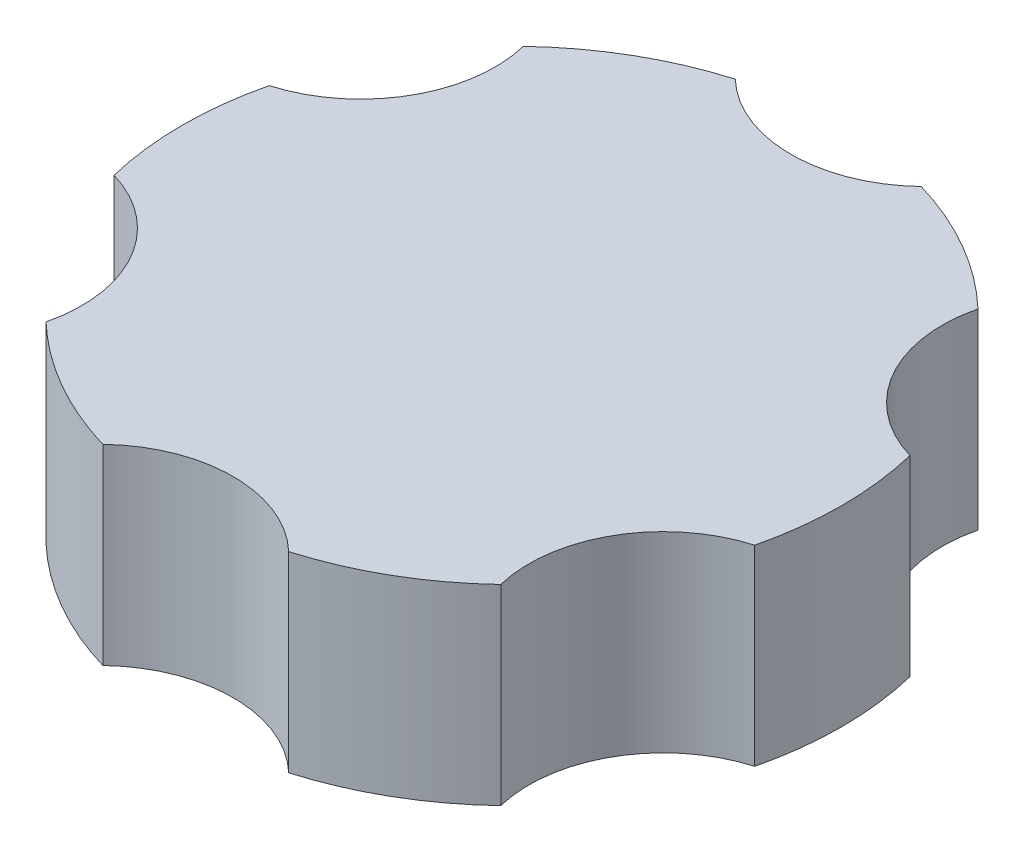
SolidWorks part; units mm, degrees
ref_plane "Alzado" through (0, 0, 0) normal (0, 0, 1) x (1, 0, 0)
ref_plane "Planta" through (0, 0, 0) normal (0, 1, 0) x (1, 0, 0)
ref_plane "Vista lateral" through (0, 0, 0) normal (1, 0, 0) x (0, 0, -1)
sketch "Croquis1" plane through (0, 0, 0) normal (0, 1, 0) x (1, 0, 0)
  line L0 (0, 0) -> (0, 24.75) construction
  line L1 (0, 24.75) -> (0, 28.0624) construction
  line L2 (-8.25, 28.0624) -> (8.25, 28.0624) construction
  line L3 (0, 0) -> (21.4341, 12.375) construction
  arc A0 (8.25, -28.0624) -> (20.1778, -21.1759) centre (0, 0) ccw
  arc A2 (-8.25, 28.0624) -> (8.25, 28.0624) centre (0, 36.68) ccw
  arc A3 (20.1778, 21.1759) -> (28.4278, 6.8865) centre (31.7658, 18.34) ccw
  arc A4 (28.4278, -6.8865) -> (20.1778, -21.1759) centre (31.7658, -18.34) ccw
  arc A5 (8.25, -28.0624) -> (-8.25, -28.0624) centre (0, -36.68) ccw
  arc A6 (-20.1778, -21.1759) -> (-28.4278, -6.8865) centre (-31.7658, -18.34) ccw
  arc A7 (-28.4278, 6.8865) -> (-20.1778, 21.1759) centre (-31.7658, 18.34) ccw
  arc A8 (28.4278, -6.8865) -> (28.4278, 6.8865) centre (0, 0) ccw
  arc A9 (-20.1778, -21.1759) -> (-8.25, -28.0624) centre (0, 0) ccw
  arc A10 (-28.4278, 6.8865) -> (-28.4278, -6.8865) centre (0, 0) ccw
  arc A11 (-8.25, 28.0624) -> (-20.1778, 21.1759) centre (0, 0) ccw
  arc A12 (20.1778, 21.1759) -> (8.25, 28.0624) centre (0, 0) ccw
  point P4 (0, 28.0624)
  point P25 (0, 0)
  dimension "D1" = 16.5
  dimension "D2" = 58.5
  dimension "D4" = 60
  dimension "D5" = 6
extrude "Saliente-Extruir1" add sketch "Croquis1" along normal blind 17
